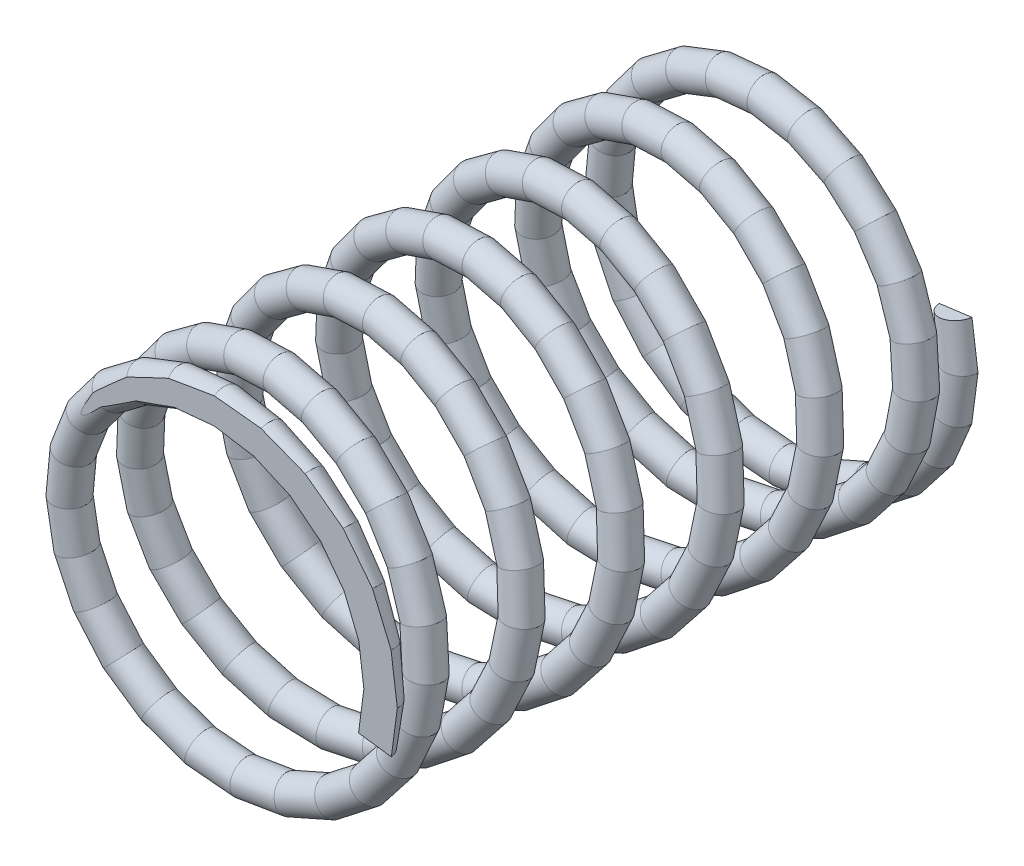
SolidWorks part; units mm, degrees
ref_plane "前视基准面" through (0, 0, 0) normal (0, 0, 1) x (1, 0, 0)
ref_plane "上视基准面" through (0, 0, 0) normal (0, 1, 0) x (1, 0, 0)
ref_plane "右视基准面" through (0, 0, 0) normal (1, 0, 0) x (0, 0, -1)
ref_plane "基准面1" through (0, 0, 70) normal (0, 0, 1) x (1, 0, 0)
sketch3d "3D草图2"
  line L0 (19.3185, 5.1764, -0.2083) -> (20, 0, 0)
  line L1 (20, 0, 0) -> (19.3185, -5.1764, 0.2083)
  line L2 (19.3185, -5.1764, 0.2083) -> (17.3205, -10, 0.4167)
  line L3 (17.3205, -10, 0.4167) -> (14.1421, -14.1421, 0.625)
  line L4 (14.1421, -14.1421, 0.625) -> (10, -17.3205, 0.8333)
  line L5 (10, -17.3205, 0.8333) -> (5.1764, -19.3185, 1.0417)
  line L6 (5.1764, -19.3185, 1.0417) -> (0, -20, 1.25)
  line L7 (0, -20, 1.25) -> (-5.1764, -19.3185, 1.4583)
  line L8 (-5.1764, -19.3185, 1.4583) -> (-10, -17.3205, 1.6667)
  line L9 (-10, -17.3205, 1.6667) -> (-14.1421, -14.1421, 1.875)
  line L10 (-14.1421, -14.1421, 1.875) -> (-17.3205, -10, 2.0833)
  line L11 (-17.3205, -10, 2.0833) -> (-19.3185, -5.1764, 2.2917)
  line L12 (-19.3185, -5.1764, 2.2917) -> (-20, 0, 2.5)
  line L13 (-20, 0, 2.5) -> (-19.3185, 5.1764, 2.7083)
  line L14 (-19.3185, 5.1764, 2.7083) -> (-17.3205, 10, 2.9167)
  line L15 (-17.3205, 10, 2.9167) -> (-14.1421, 14.1421, 3.125)
  line L16 (-14.1421, 14.1421, 3.125) -> (-10, 17.3205, 3.3333)
  line L17 (-10, 17.3205, 3.3333) -> (-5.1764, 19.3185, 3.5417)
  line L18 (-5.1764, 19.3185, 3.5417) -> (0, 20, 3.75)
  line L19 (0, 20, 3.75) -> (5.1764, 19.3185, 3.9705)
  line L20 (5.1764, 19.3185, 3.9705) -> (10, 17.3205, 4.2153)
  line L21 (10, 17.3205, 4.2153) -> (14.1421, 14.1421, 4.4844)
  line L22 (14.1421, 14.1421, 4.4844) -> (17.3205, 10, 4.7778)
  line L23 (17.3205, 10, 4.7778) -> (19.3185, 5.1764, 5.0955)
  line L24 (19.3185, 5.1764, 5.0955) -> (20, 0, 5.4375)
  line L25 (20, 0, 5.4375) -> (19.3185, -5.1764, 5.803)
  line L26 (19.3185, -5.1764, 5.803) -> (17.3205, -10, 6.1944)
  line L27 (17.3205, -10, 6.1944) -> (14.1421, -14.1421, 6.6094)
  line L28 (14.1421, -14.1421, 6.6094) -> (10, -17.3205, 7.0486)
  line L29 (10, -17.3205, 7.0486) -> (5.1764, -19.3185, 7.5122)
  line L30 (5.1764, -19.3185, 7.5122) -> (0, -20, 8)
  line L31 (0, -20, 8) -> (-5.1764, -19.3185, 8.5)
  line L32 (-5.1764, -19.3185, 8.5) -> (-10, -17.3205, 9)
  line L33 (-10, -17.3205, 9) -> (-14.1421, -14.1421, 9.5)
  line L34 (-14.1421, -14.1421, 9.5) -> (-17.3205, -10, 10)
  line L35 (-17.3205, -10, 10) -> (-19.3185, -5.1764, 10.5)
  line L36 (-19.3185, -5.1764, 10.5) -> (-20, 0, 11)
  line L37 (-20, 0, 11) -> (-19.3185, 5.1764, 11.5)
  line L38 (-19.3185, 5.1764, 11.5) -> (-17.3205, 10, 12)
  line L39 (-17.3205, 10, 12) -> (-14.1421, 14.1421, 12.5)
  line L40 (-14.1421, 14.1421, 12.5) -> (-10, 17.3205, 13)
  line L41 (-10, 17.3205, 13) -> (-5.1764, 19.3185, 13.5)
  line L42 (-5.1764, 19.3185, 13.5) -> (0, 20, 14)
  line L43 (0, 20, 14) -> (5.1764, 19.3185, 14.5)
  line L44 (5.1764, 19.3185, 14.5) -> (10, 17.3205, 15)
  line L45 (10, 17.3205, 15) -> (14.1421, 14.1421, 15.5)
  line L46 (14.1421, 14.1421, 15.5) -> (17.3205, 10, 16)
  line L47 (17.3205, 10, 16) -> (19.3185, 5.1764, 16.5)
  line L48 (19.3185, 5.1764, 16.5) -> (20, 0, 17)
  line L49 (20, 0, 17) -> (19.3185, -5.1764, 17.5)
  line L50 (19.3185, -5.1764, 17.5) -> (17.3205, -10, 18)
  line L51 (17.3205, -10, 18) -> (14.1421, -14.1421, 18.5)
  line L52 (14.1421, -14.1421, 18.5) -> (10, -17.3205, 19)
  line L53 (10, -17.3205, 19) -> (5.1764, -19.3185, 19.5)
  line L54 (5.1764, -19.3185, 19.5) -> (0, -20, 20)
  line L55 (0, -20, 20) -> (-5.1764, -19.3185, 20.5)
  line L56 (-5.1764, -19.3185, 20.5) -> (-10, -17.3205, 21)
  line L57 (-10, -17.3205, 21) -> (-14.1421, -14.1421, 21.5)
  line L58 (-14.1421, -14.1421, 21.5) -> (-17.3205, -10, 22)
  line L59 (-17.3205, -10, 22) -> (-19.3185, -5.1764, 22.5)
  line L60 (-19.3185, -5.1764, 22.5) -> (-20, 0, 23)
  line L61 (-20, 0, 23) -> (-19.3185, 5.1764, 23.5)
  line L62 (-19.3185, 5.1764, 23.5) -> (-17.3205, 10, 24)
  line L63 (-17.3205, 10, 24) -> (-14.1421, 14.1421, 24.5)
  line L64 (-14.1421, 14.1421, 24.5) -> (-10, 17.3205, 25)
  line L65 (-10, 17.3205, 25) -> (-5.1764, 19.3185, 25.5)
  line L66 (-5.1764, 19.3185, 25.5) -> (0, 20, 26)
  line L67 (0, 20, 26) -> (5.1764, 19.3185, 26.5)
  line L68 (5.1764, 19.3185, 26.5) -> (10, 17.3205, 27)
  line L69 (10, 17.3205, 27) -> (14.1421, 14.1421, 27.5)
  line L70 (14.1421, 14.1421, 27.5) -> (17.3205, 10, 28)
  line L71 (17.3205, 10, 28) -> (19.3185, 5.1764, 28.5)
  line L72 (19.3185, 5.1764, 28.5) -> (20, 0, 29)
  line L73 (20, 0, 29) -> (19.3185, -5.1764, 29.5)
  line L74 (19.3185, -5.1764, 29.5) -> (17.3205, -10, 30)
  line L75 (17.3205, -10, 30) -> (14.1421, -14.1421, 30.5)
  line L76 (14.1421, -14.1421, 30.5) -> (10, -17.3205, 31)
  line L77 (10, -17.3205, 31) -> (5.1764, -19.3185, 31.5)
  line L78 (5.1764, -19.3185, 31.5) -> (0, -20, 32)
  line L79 (0, -20, 32) -> (-5.1764, -19.3185, 32.5)
  line L80 (-5.1764, -19.3185, 32.5) -> (-10, -17.3205, 33)
  line L81 (-10, -17.3205, 33) -> (-14.1421, -14.1421, 33.5)
  line L82 (-14.1421, -14.1421, 33.5) -> (-17.3205, -10, 34)
  line L83 (-17.3205, -10, 34) -> (-19.3185, -5.1764, 34.5)
  line L84 (-19.3185, -5.1764, 34.5) -> (-20, 0, 35)
  line L85 (-20, 0, 35) -> (-19.3185, 5.1764, 35.5)
  line L86 (-19.3185, 5.1764, 35.5) -> (-17.3205, 10, 36)
  line L87 (-17.3205, 10, 36) -> (-14.1421, 14.1421, 36.5)
  line L88 (-14.1421, 14.1421, 36.5) -> (-10, 17.3205, 37)
  line L89 (-10, 17.3205, 37) -> (-5.1764, 19.3185, 37.5)
  line L90 (-5.1764, 19.3185, 37.5) -> (0, 20, 38)
  line L91 (0, 20, 38) -> (5.1764, 19.3185, 38.5)
  line L92 (5.1764, 19.3185, 38.5) -> (10, 17.3205, 39)
  line L93 (10, 17.3205, 39) -> (14.1421, 14.1421, 39.5)
  line L94 (14.1421, 14.1421, 39.5) -> (17.3205, 10, 40)
  line L95 (17.3205, 10, 40) -> (19.3185, 5.1764, 40.5)
  line L96 (19.3185, 5.1764, 40.5) -> (20, 0, 41)
  line L97 (20, 0, 41) -> (19.3185, -5.1764, 41.5)
  line L98 (19.3185, -5.1764, 41.5) -> (17.3205, -10, 42)
  line L99 (17.3205, -10, 42) -> (14.1421, -14.1421, 42.5)
  line L100 (14.1421, -14.1421, 42.5) -> (10, -17.3205, 43)
  line L101 (10, -17.3205, 43) -> (5.1764, -19.3185, 43.5)
  line L102 (5.1764, -19.3185, 43.5) -> (0, -20, 44)
  line L103 (0, -20, 44) -> (-5.1764, -19.3185, 44.5)
  line L104 (-5.1764, -19.3185, 44.5) -> (-10, -17.3205, 45)
  line L105 (-10, -17.3205, 45) -> (-14.1421, -14.1421, 45.5)
  line L106 (-14.1421, -14.1421, 45.5) -> (-17.3205, -10, 46)
  line L107 (-17.3205, -10, 46) -> (-19.3185, -5.1764, 46.5)
  line L108 (-19.3185, -5.1764, 46.5) -> (-20, 0, 47)
  line L109 (-20, 0, 47) -> (-19.3185, 5.1764, 47.5)
  line L110 (-19.3185, 5.1764, 47.5) -> (-17.3205, 10, 48)
  line L111 (-17.3205, 10, 48) -> (-14.1421, 14.1421, 48.5)
  line L112 (-14.1421, 14.1421, 48.5) -> (-10, 17.3205, 49)
  line L113 (-10, 17.3205, 49) -> (-5.1764, 19.3185, 49.5)
  line L114 (-5.1764, 19.3185, 49.5) -> (0, 20, 50)
  line L115 (0, 20, 50) -> (5.1764, 19.3185, 50.5)
  line L116 (5.1764, 19.3185, 50.5) -> (10, 17.3205, 51)
  line L117 (10, 17.3205, 51) -> (14.1421, 14.1421, 51.5)
  line L118 (14.1421, 14.1421, 51.5) -> (17.3205, 10, 52)
  line L119 (17.3205, 10, 52) -> (19.3185, 5.1764, 52.5)
  line L120 (19.3185, 5.1764, 52.5) -> (20, 0, 53)
  line L121 (20, 0, 53) -> (19.3185, -5.1764, 53.5)
  line L122 (19.3185, -5.1764, 53.5) -> (17.3205, -10, 54)
  line L123 (17.3205, -10, 54) -> (14.1421, -14.1421, 54.5)
  line L124 (14.1421, -14.1421, 54.5) -> (10, -17.3205, 55)
  line L125 (10, -17.3205, 55) -> (5.1764, -19.3185, 55.5)
  line L126 (5.1764, -19.3185, 55.5) -> (0, -20, 56)
  line L127 (0, -20, 56) -> (-5.1764, -19.3185, 56.5)
  line L128 (-5.1764, -19.3185, 56.5) -> (-10, -17.3205, 57)
  line L129 (-10, -17.3205, 57) -> (-14.1421, -14.1421, 57.5)
  line L130 (-14.1421, -14.1421, 57.5) -> (-17.3205, -10, 58)
  line L131 (-17.3205, -10, 58) -> (-19.3185, -5.1764, 58.5)
  line L132 (-19.3185, -5.1764, 58.5) -> (-20, 0, 59)
  line L133 (-20, 0, 59) -> (-19.3185, 5.1764, 59.5)
  line L134 (-19.3185, 5.1764, 59.5) -> (-17.3205, 10, 60)
  line L135 (-17.3205, 10, 60) -> (-14.1421, 14.1421, 60.5)
  line L136 (-14.1421, 14.1421, 60.5) -> (-10, 17.3205, 61)
  line L137 (-10, 17.3205, 61) -> (-5.1764, 19.3185, 61.5)
  line L138 (-5.1764, 19.3185, 61.5) -> (0, 20, 62)
  line L139 (0, 20, 62) -> (5.1764, 19.3185, 62.4878)
  line L140 (5.1764, 19.3185, 62.4878) -> (10, 17.3205, 62.9514)
  line L141 (10, 17.3205, 62.9514) -> (14.1421, 14.1421, 63.3906)
  line L142 (14.1421, 14.1421, 63.3906) -> (17.3205, 10, 63.8056)
  line L143 (17.3205, 10, 63.8056) -> (19.3185, 5.1764, 64.1962)
  line L144 (19.3185, 5.1764, 64.1962) -> (20, 0, 64.5625)
  line L145 (20, 0, 64.5625) -> (19.3185, -5.1764, 64.9045)
  line L146 (19.3185, -5.1764, 64.9045) -> (17.3205, -10, 65.2222)
  line L147 (17.3205, -10, 65.2222) -> (14.1421, -14.1421, 65.5156)
  line L148 (14.1421, -14.1421, 65.5156) -> (10, -17.3205, 65.7847)
  line L149 (10, -17.3205, 65.7847) -> (5.1764, -19.3185, 66.0295)
  line L150 (5.1764, -19.3185, 66.0295) -> (0, -20, 66.25)
  line L151 (0, -20, 66.25) -> (-5.1764, -19.3185, 66.4583)
  line L152 (-5.1764, -19.3185, 66.4583) -> (-10, -17.3205, 66.6667)
  line L153 (-10, -17.3205, 66.6667) -> (-14.1421, -14.1421, 66.875)
  line L154 (-14.1421, -14.1421, 66.875) -> (-17.3205, -10, 67.0833)
  line L155 (-17.3205, -10, 67.0833) -> (-19.3185, -5.1764, 67.2917)
  line L156 (-19.3185, -5.1764, 67.2917) -> (-20, 0, 67.5)
  line L157 (-20, 0, 67.5) -> (-19.3185, 5.1764, 67.7083)
  line L158 (-19.3185, 5.1764, 67.7083) -> (-17.3205, 10, 67.9167)
  line L159 (-17.3205, 10, 67.9167) -> (-14.1421, 14.1421, 68.125)
  line L160 (-14.1421, 14.1421, 68.125) -> (-10, 17.3205, 68.3333)
  line L161 (-10, 17.3205, 68.3333) -> (-5.1764, 19.3185, 68.5417)
  line L162 (-5.1764, 19.3185, 68.5417) -> (0, 20, 68.75)
  line L163 (0, 20, 68.75) -> (5.1764, 19.3185, 68.9583)
  line L164 (5.1764, 19.3185, 68.9583) -> (10, 17.3205, 69.1667)
  line L165 (10, 17.3205, 69.1667) -> (14.1421, 14.1421, 69.375)
  line L166 (14.1421, 14.1421, 69.375) -> (17.3205, 10, 69.5833)
  line L167 (17.3205, 10, 69.5833) -> (19.3185, 5.1764, 69.7917)
  line L168 (19.3185, 5.1764, 69.7917) -> (20, 0, 70)
  line L169 (20, 0, 70) -> (19.3185, -5.1764, 70.2083)
sweep "扫描4" add path "3D草图2" circular profile diameter 4 parameters "D3"=4
sketch "草图8" plane through (0, 0, 0) normal (0, 0, 1) x (1, 0, 0)
  line L0 (-50, -50) -> (50, -50)
  line L1 (50, -50) -> (50, 50)
  line L2 (50, 50) -> (-50, 50)
  line L3 (-50, 50) -> (-50, -50)
extrude "切除-拉伸3" cut sketch "草图8" against normal blind 10
sketch "草图9" plane through (0, 0, 70) normal (0, 0, 1) x (1, 0, 0)
  line L0 (-50, -50) -> (50, -50)
  line L1 (50, -50) -> (50, 50)
  line L2 (50, 50) -> (-50, 50)
  line L3 (-50, 50) -> (-50, -50)
extrude "切除-拉伸4" cut sketch "草图9" along normal blind 10
